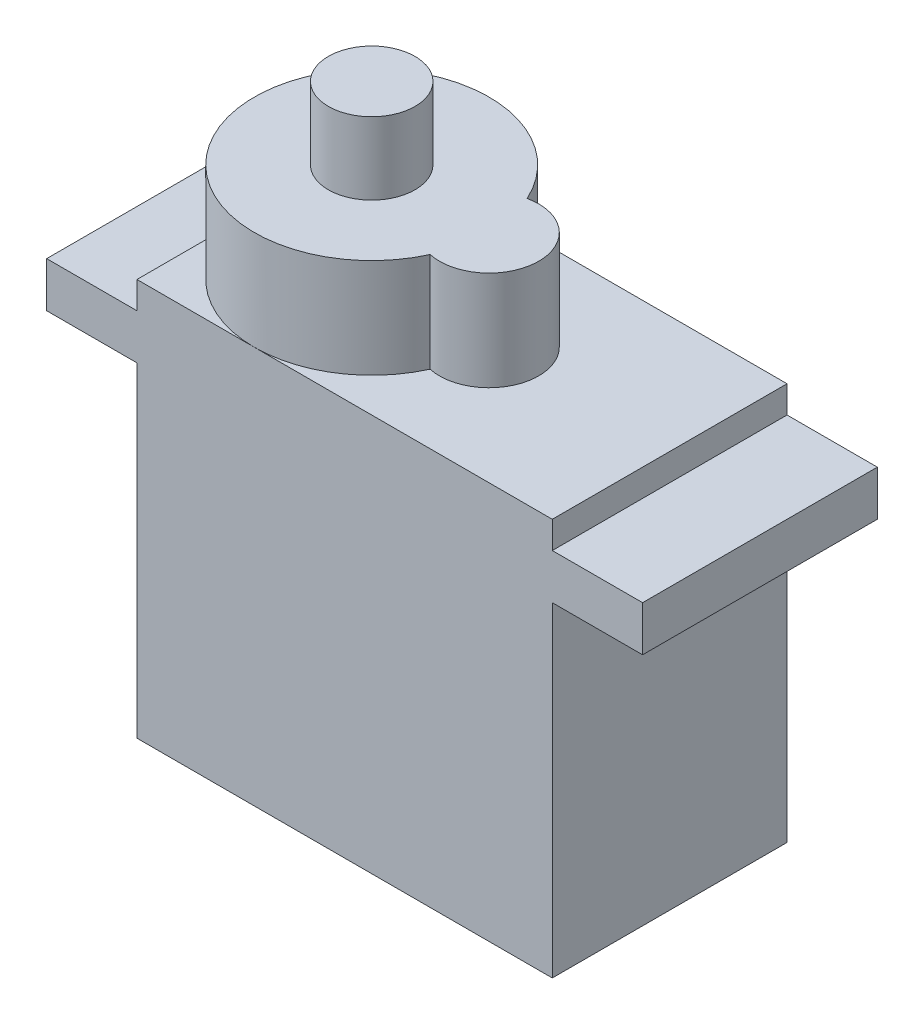
SolidWorks part; units mm, degrees
ref_plane "Front Plane" through (0, 0, 0) normal (0, 0, 1) x (1, 0, 0)
ref_plane "Top Plane" through (0, 0, 0) normal (0, 1, 0) x (1, 0, 0)
ref_plane "Right Plane" through (0, 0, 0) normal (1, 0, 0) x (0, 0, -1)
sketch "Sketch1" plane through (0, 0, 0) normal (0, 1, 0) x (1, 0, 0)
  line L1 (-11.5, 6.5) -> (11.5, 6.5)
  line L2 (-11.5, 6.5) -> (-11.5, -6.5)
  line L3 (-11.5, -6.5) -> (11.5, -6.5)
  line L4 (11.5, 6.5) -> (11.5, -6.5)
  line L5 (-11.5, 6.5) -> (11.5, -6.5) construction
  line L6 (-11.5, -6.5) -> (11.5, 6.5) construction
  point P0 (0, 0)
  dimension "D1" = 23
  dimension "D2" = 13
extrude "Boss-Extrude1" add sketch "Sketch1" along normal blind 18
sketch "Sketch2" plane through (0, 18, 0) normal (0, 1, 0) x (1, 0, 0)
  line L0 (11.5, 6.5) -> (-11.5, 6.5) construction
  line L1 (-16.5, 6.5) -> (16.5, 6.5)
  line L2 (-16.5, 6.5) -> (-16.5, -6.5)
  line L3 (-16.5, -6.5) -> (16.5, -6.5)
  line L4 (16.5, 6.5) -> (16.5, -6.5)
  line L5 (-16.5, 6.5) -> (16.5, -6.5) construction
  line L6 (-16.5, -6.5) -> (16.5, 6.5) construction
  line L7 (-11.5, 6.5) -> (-11.5, -6.5) construction
  point P0 (0, 0)
  dimension "D1" = 5
extrude "Boss-Extrude2" add sketch "Sketch2" along normal blind 2.5
sketch "Sketch3" plane through (0, 20.5, 0) normal (0, 1, 0) x (1, 0, 0)
  line L0 (-16.5, -6.5) -> (16.5, -6.5) construction
  line L1 (-11.5, 6.5) -> (11.5, 6.5)
  line L2 (-11.5, 6.5) -> (-11.5, -6.5)
  line L3 (-11.5, -6.5) -> (11.5, -6.5)
  line L4 (11.5, 6.5) -> (11.5, -6.5)
  line L5 (-11.5, 6.5) -> (11.5, -6.5) construction
  line L6 (-11.5, -6.5) -> (11.5, 6.5) construction
  point P0 (0, 0)
  dimension "D1" = 23
extrude "Boss-Extrude3" add sketch "Sketch3" along normal blind 1.5
sketch "Sketch4" plane through (0, 22, 0) normal (0, 1, 0) x (1, 0, 0)
  line L0 (-11.5, 6.5) -> (-11.5, -6.5) construction
  line L1 (11.5, 6.5) -> (-11.5, 6.5) construction
  line L2 (-11.5, -6.5) -> (11.5, -6.5) construction
  arc A0 (0.9183, 2.6878) -> (0.9183, -2.6878) centre (-5, 0) ccw
  arc A1 (0.9183, -2.6878) -> (0.9183, 2.6878) centre (1.5, 0) ccw
  dimension "D1" = 5.5
extrude "Boss-Extrude4" add sketch "Sketch4" along normal blind 5.5
sketch "Sketch5" plane through (0, 27.5, 0) normal (0, 1, 0) x (1, 0, 0)
  circle A0 centre (-5, 0) radius 2.4
  arc A1 (0.9183, 2.6878) -> (-5, 6.5) centre (-5, 0) ccw construction
  dimension "D1" = 4.8
extrude "Boss-Extrude5" add sketch "Sketch5" along normal blind 4
